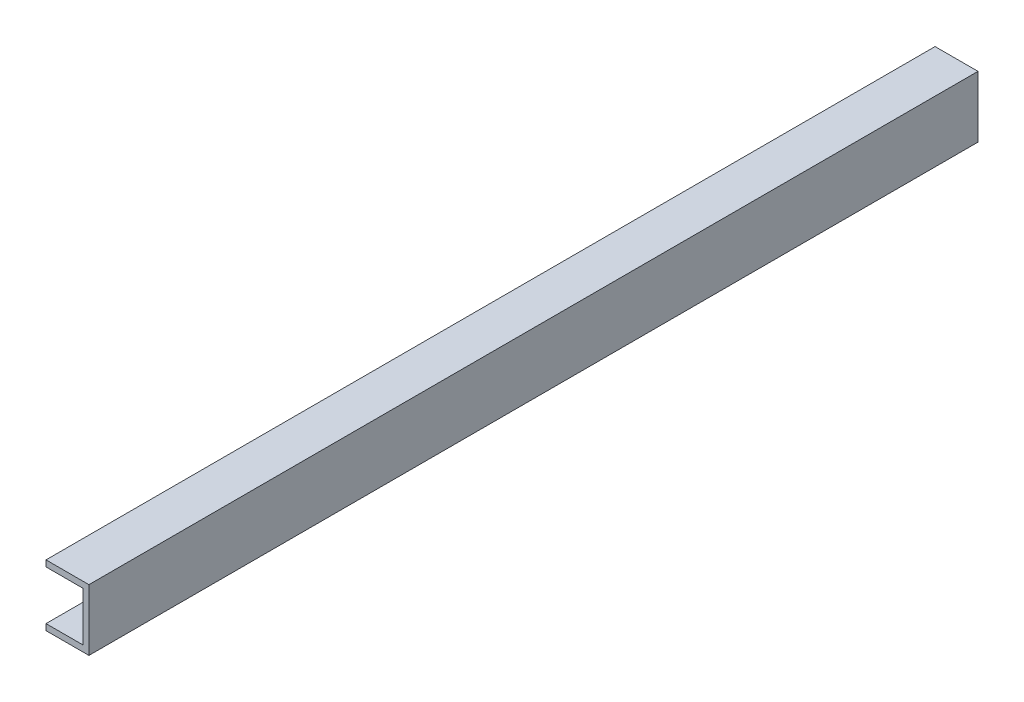
SolidWorks part; units mm, degrees
ref_plane "Front Plane" through (0, 0, 0) normal (0, 0, 1) x (1, 0, 0)
ref_plane "Top Plane" through (0, 0, 0) normal (0, 1, 0) x (1, 0, 0)
ref_plane "Right Plane" through (0, 0, 0) normal (1, 0, 0) x (0, 0, -1)
sketch "Sketch1" plane through (0, 0, 0) normal (0, 0, 1) x (1, 0, 0)
  line L0 (0, 0) -> (14, 0)
  line L1 (14, 0) -> (14, 20)
  line L2 (14, 20) -> (0, 20)
  line L3 (0, 20) -> (0, 18)
  line L4 (0, 18) -> (12, 18)
  line L5 (12, 18) -> (12, 2)
  line L6 (12, 2) -> (0, 2)
  line L7 (0, 2) -> (0, 0)
extrude "Boss-Extrude1" add sketch "Sketch1" along normal blind 290
